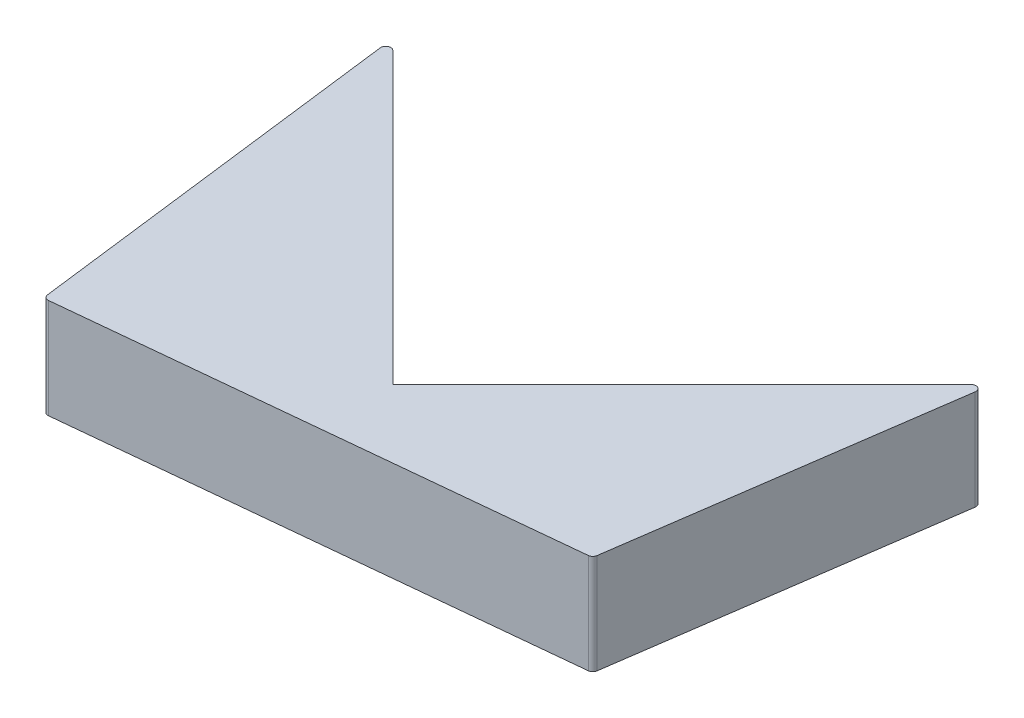
SolidWorks part; units mm, degrees
ref_plane "Front Plane" through (0, 0, 0) normal (0, 0, 1) x (1, 0, 0)
ref_plane "Top Plane" through (0, 0, 0) normal (0, 1, 0) x (1, 0, 0)
ref_plane "Right Plane" through (0, 0, 0) normal (1, 0, 0) x (0, 0, -1)
sketch "Sketch1" plane through (0, 0, 0) normal (0, 1, 0) x (1, 0, 0)
  line L0 (0, 0) -> (30, 30)
  line L1 (30, 30) -> (25, -5)
  line L2 (25, -5) -> (-25, -10)
  line L3 (-25, -10) -> (-30, 30)
  line L4 (-30, 30) -> (0, 0)
  point P5 (0, 0)
  point P6 (0, 0)
  dimension "D1" = 30
  dimension "D2" = 30
  dimension "D3" = 25
  dimension "D4" = 5
  dimension "D5" = 25
  dimension "D6" = 10
  dimension "D7" = 30
  dimension "D8" = 30
extrude "Boss-Extrude1" add sketch "Sketch1" along normal blind 10
fillet "Fillet1" radius 0.5 4 edges at (30, 5, -30) (25, 5, 5) (-30, 5, -30) (-25, 5, 10)
